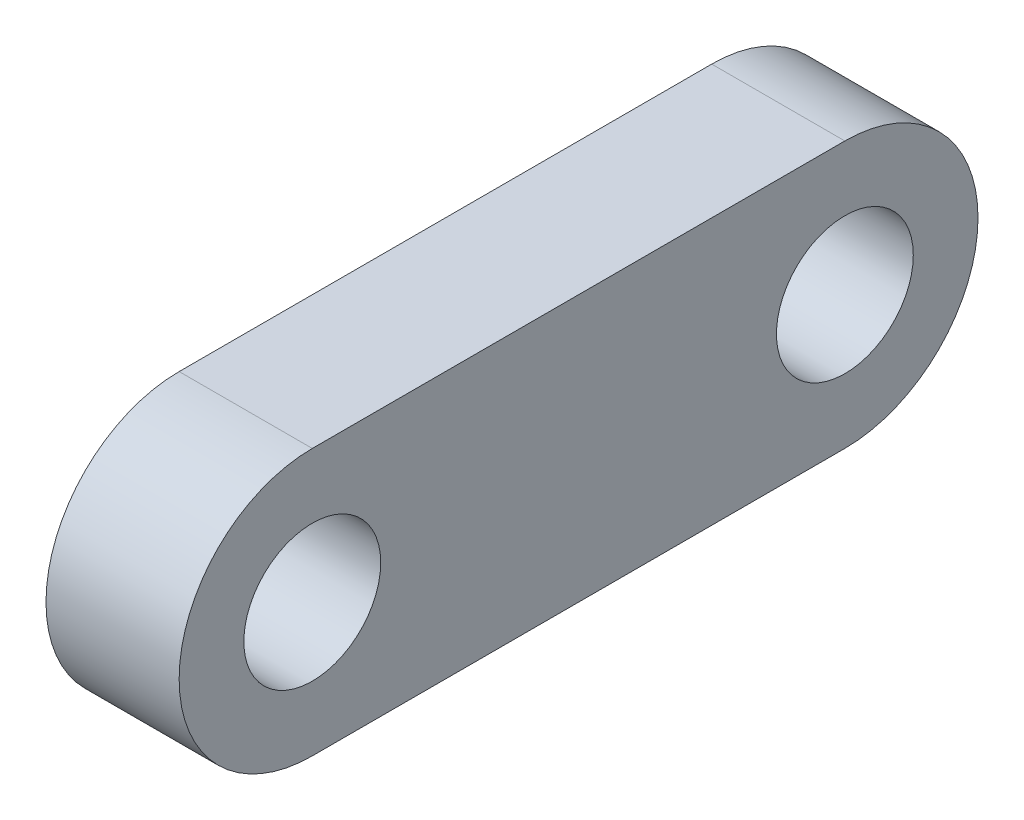
SolidWorks part; units mm, degrees
ref_plane "Front" through (0, 0, 0) normal (0, 0, 1) x (1, 0, 0)
ref_plane "Top" through (0, 0, 0) normal (0, 1, 0) x (1, 0, 0)
ref_plane "Right" through (0, 0, 0) normal (1, 0, 0) x (0, 0, -1)
sketch "Sketch1" plane through (0, 0, 0) normal (1, 0, 0) x (0, 0, -1)
  line L0 (-12.7, 0) -> (12.7, 0) construction
  line L1 (-12.7, 6.35) -> (12.7, 6.35)
  line L2 (-12.7, -6.35) -> (12.7, -6.35)
  arc A0 (-12.7, 6.35) -> (-12.7, -6.35) centre (-12.7, 0) ccw
  arc A1 (12.7, -6.35) -> (12.7, 6.35) centre (12.7, 0) ccw
  circle A2 centre (-12.7, 0) radius 12.7 construction
  circle A3 centre (12.7, 0) radius 12.7 construction
  point P2 (0, 0)
  dimension "D1" = 25.4
  dimension "D2" = 12.7
extrude "Boss-Extrude1" add sketch "Sketch1" along normal blind 6.35
hole_wizard "5/16-18 Tapped Hole1" positions "Sketch2" profile "Sketch3" tap size "5/16-18" standard "ANSI Inch" end condition through all
sketch "Sketch2" plane through (6.35, 0, 0) normal (1, 0, 0) x (0, 0, -1)
  point P0 (-12.7, 0)
  point P2 (12.7, 0)
  point P5 (-12.7, 0)
  point P7 (12.7, 0)
sketch "Sketch3" plane through (6.35, 0, 12.7) normal (0, 1, 0) x (0, 0, -1)
  line L0 (0, 0) -> (0, 6.35)
  line L1 (0, 6.35) -> (3.2639, 6.35)
  line L2 (3.2639, 6.35) -> (3.2639, 0)
  line L5 (3.2639, 0) -> (0, 0)
  line L11 (0, -6.35) -> (0, 107.95) construction
  dimension "Thru Tap Drill Dia." = 6.5278
  dimension "Thru Tap Drill Depth" = 6.35
cosmetic thread "Hole Thread1" parameters "D2"=7.9375
cosmetic thread "Hole Thread2" parameters "D2"=7.9375
